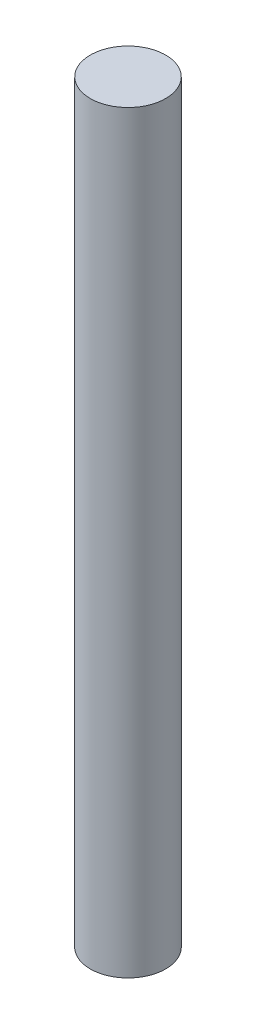
SolidWorks part; units mm, degrees
ref_plane "Спереди" through (0, 0, 0) normal (0, 0, 1) x (1, 0, 0)
ref_plane "Сверху" through (0, 0, 0) normal (0, 1, 0) x (1, 0, 0)
ref_plane "Справа" through (0, 0, 0) normal (1, 0, 0) x (0, 0, -1)
other "Configuration Table"
sketch "Эскиз1" plane through (0, 0, 0) normal (0, 1, 0) x (1, 0, 0)
  circle A0 centre (0, 0) radius 10
  dimension "D1" = 20
extrude "Бобышка-Вытянуть1" add sketch "Эскиз1" along normal blind 200
